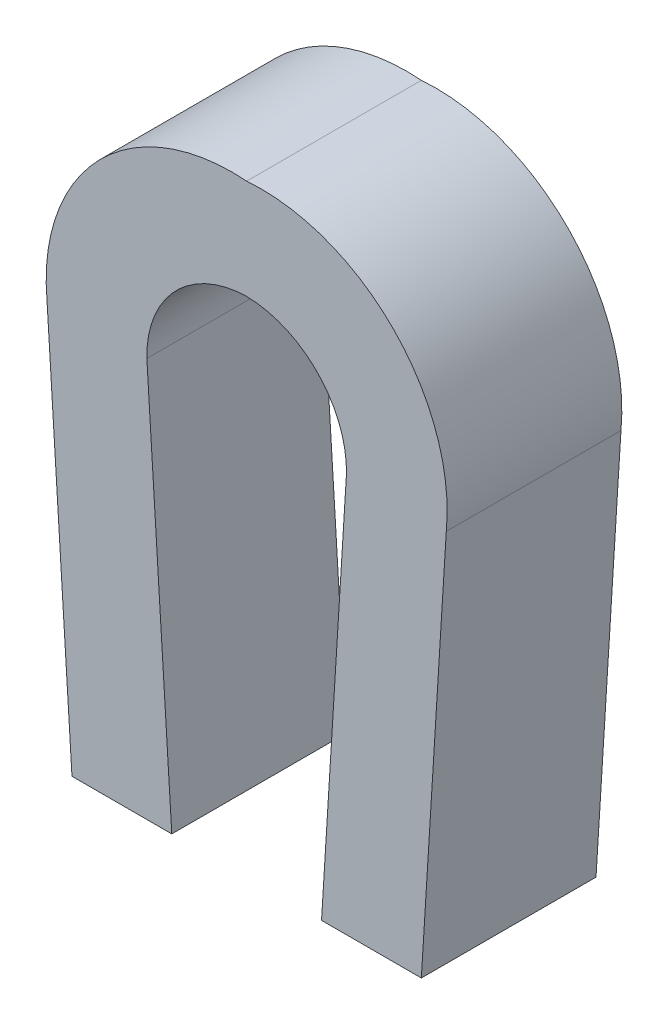
SolidWorks part; units mm, degrees
ref_plane "Front Plane" through (0, 0, 0) normal (0, 0, 1) x (1, 0, 0)
ref_plane "Top Plane" through (0, 0, 0) normal (0, 1, 0) x (1, 0, 0)
ref_plane "Right Plane" through (0, 0, 0) normal (1, 0, 0) x (0, 0, -1)
sketch "Sketch1" plane through (0, 0, 0) normal (0, 0, 1) x (1, 0, 0)
  line L0 (-2, 4) -> (-1.5, -4)
  line L5 (-1.5, -4) -> (-3.5, -4)
  line L6 (-3.5, -4) -> (-4, 4)
  line L10 (0, 7.8443) -> (0, -6.8113) construction
  line L11 (3.5, -4) -> (4, 4)
  line L12 (1.5, -4) -> (3.5, -4)
  line L13 (2, 4) -> (1.5, -4)
  arc A4 (-2, 4) -> (0, 6.0772) centre (0.036, 4.0411) cw
  arc A5 (-4, 4) -> (0, 8.0772) centre (-0.2889, 4.3599) cw
  arc A6 (4, 4) -> (0, 8.0772) centre (0.2889, 4.3599) ccw
  arc A7 (2, 4) -> (0, 6.0772) centre (-0.036, 4.0411) ccw
  point P6 (0, 6.0772)
  dimension "D1" = 8
  dimension "D2" = 2
  dimension "D3" = 2
  dimension "D4" = 2
  dimension "D6" = 1.5
extrude "Boss-Extrude1" add sketch "Sketch1" along normal blind 3.5
